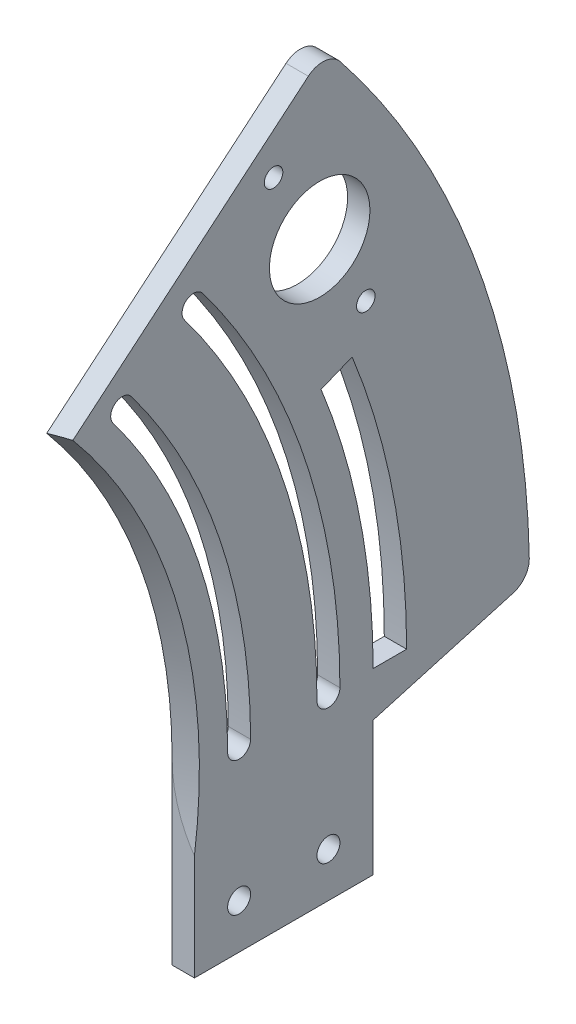
SolidWorks part; units mm, degrees
material "ABS"
ref_plane "Front Plane" through (0, 0, 0) normal (0, 0, 1) x (1, 0, 0)
ref_plane "Top Plane" through (0, 0, 0) normal (0, 1, 0) x (1, 0, 0)
ref_plane "Right Plane" through (0, 0, 0) normal (1, 0, 0) x (0, 0, -1)
sketch "Sketch1" plane through (0, 0, 0) normal (1, 0, 0) x (0, 0, -1)
  line L0 (-1000, 0) -> (49000, 0) construction
  line L1 (0, 0) -> (116.7452, 97.9608) construction
  line L2 (0, 0) -> (59.8729, -43.5002) construction
  line L3 (152.4, 0) -> (152.4, -50.8)
  line L5 (152.4, -50.8) -> (203.2, -50.8)
  line L6 (203.2, -50.8) -> (203.2, 0)
  line L7 (155.6602, 130.6144) -> (189.7109, 159.1864)
  line L8 (-23.5062, -9.499) -> (46248.5759, 18689.3257) construction
  line L9 (188.3985, 76.133) -> (229.6107, 92.7871)
  line L10 (0, 0) -> (188.0059, 113.3006) construction
  line L11 (186.339, 99.7277) -> (-5908.5361, -49527.4069) construction
  line L12 (188.0059, 113.3006) -> (49815.1406, -5981.5745) construction
  line L13 (0, 0) -> (190.9455, 69.4985) construction
  line L16 (116.7452, 97.9608) -> (155.6602, 130.6144)
  line L17 (190.9455, 69.4985) -> (202.8796, 73.8421) construction
  line L20 (190.9455, 69.4985) -> (196.9126, 71.6703) construction
  line L21 (188.0059, 113.3006) -> (-25619.9772, 42937.9197) construction
  arc A0 (152.4, 0) -> (116.7452, 97.9608) centre (0, 0) ccw
  arc A2 (189.7109, 159.1864) -> (229.6107, 92.7871) centre (0, 0) cw
  circle A3 centre (188.0059, 113.3006) radius 14.2875
  circle A4 centre (188.0059, 113.3006) radius 25.4 construction
  circle A12 centre (174.8954, 135.0555) radius 2.6289
  arc A13 (190.9455, 69.4985) -> (203.2, 0) centre (0, 0) cw
  arc A14 (190.9455, 69.4985) -> (188.3985, 76.133) centre (0, 0) ccw
  circle A15 centre (201.1164, 91.5456) radius 2.6289
  point P9 (183.2534, 74.6033)
  dimension "D1" = 304.8
  dimension "D11" = 28.575
  dimension "D12" = 50.8
  dimension "D14" = 50.8
  dimension "D15" = 9.525
  dimension "D7" = 5.2578
  dimension "D8" = 5.2578
  dimension "D2" = 40
  dimension "D3" = 36
  dimension "D4" = 50.8
  dimension "D5" = 50.8
  dimension "D6" = 44.45
  dimension "D9" = 219.5068
  dimension "D10" = 8.925
  dimension "D13" = 90
  dimension "D16" = 20
  dimension "D17" = 12.7
extrude "Boss-Extrude1" add sketch "Sketch1" along normal blind 6.35
sketch "Sketch2" plane through (6.35, 0, 0) normal (1, 0, 0) x (0, 0, -1)
  line L0 (-1000, 0) -> (49000, 0) construction
  line L1 (0, 0) -> (218.1696, 164.4026) construction
  arc A1 (152.4, 0) -> (116.7452, 97.9608) centre (0, 0) ccw construction
  arc A2 (134.4614, 101.3239) -> (129.2481, 97.3954) centre (131.8547, 99.3597) ccw
  arc A3 (129.2481, 97.3954) -> (161.8361, 0) centre (0, 0) cw
  arc A4 (134.4614, 101.3239) -> (168.3639, 0) centre (0, 0) cw
  arc A5 (161.8361, 0) -> (168.3639, 0) centre (165.1, 0) ccw
  arc A6 (154.7467, 116.61) -> (149.5334, 112.6815) centre (152.1401, 114.6458) ccw
  arc A7 (149.5334, 112.6815) -> (187.2361, 0) centre (0, 0) cw
  arc A8 (154.7467, 116.61) -> (193.7639, 0) centre (0, 0) cw
  arc A9 (152.1401, 114.6458) -> (190.5, 0) centre (0, 0) cw construction
  arc A10 (187.2361, 0) -> (193.7639, 0) centre (190.5, 0) ccw
  point P9 (131.8547, 99.3597)
  point P14 (152.1401, 114.6458)
  point P19 (165.1, 0)
  dimension "D3" = 6.5278
  dimension "D5" = 6.5278
  dimension "D1" = 37
  dimension "D2" = 165.1
  dimension "D4" = 25.4
extrude "Cut-Extrude4" cut sketch "Sketch2" against normal blind 6.35
sketch "Sketch3" plane through (6.35, 0, 0) normal (1, 0, 0) x (0, 0, -1)
  line L0 (165.1, -38.1) -> (190.5, -38.1) construction
  line L1 (152.4, -50.8) -> (165.1, -50.8) construction
  line L2 (152.4, -50.8) -> (152.4, -38.1) construction
  line L3 (152.4, -38.1) -> (165.1, -38.1) construction
  line L4 (165.1, -50.8) -> (165.1, -38.1) construction
  circle A0 centre (165.1, -38.1) radius 3.2639
  circle A1 centre (190.5, -38.1) radius 3.2639
  dimension "D3" = 6.5278
  dimension "D5" = 6.5278
  dimension "D1" = 12.7
  dimension "D2" = 12.7
  dimension "D4" = 25.4
extrude "Cut-Extrude5" cut sketch "Sketch3" against normal blind 6.35
fillet "Fillet1" radius 6.35 1 edges at (3.175, 159.1864, -189.7109)
sketch "Sketch4" plane through (0, 0, 0) normal (0, 1, 0) x (1, 0, 0)
  line L0 (0, 0) -> (0, 152.4) construction
  line L1 (0, 0) -> (28.575, 0) construction
  line L2 (28.575, 0) -> (28.575, 38.1) construction
  line L3 (-89.2427, 38.1) -> (146.3927, 38.1)
  line L4 (-1000, 0) -> (49000, 0) construction
  arc A0 (146.3927, 38.1) -> (-89.2427, 38.1) centre (28.575, 38.1) ccw
  dimension "D1" = 152.4
  dimension "D2" = 28.575
  dimension "D3" = 38.1
revolve "Cut-Revolve1" cut sketch "Sketch4" angle 360 about L4
sketch "Sketch5" plane through (0, 0, 0) normal (-1, 0, 0) x (0, 0, 1)
  line L0 (-188.3985, 76.133) -> (-229.6107, 92.7871) construction
  line L1 (-197.2297, 79.7017) -> (-229.6107, 92.7871)
  line L2 (-247.65, 0) -> (-212.725, 0) construction
  line L3 (-212.725, 0) -> (-203.2, 0)
  line L4 (-247.65, 0) -> (-203.2, -12.7)
  line L5 (-203.2, -50.8) -> (-203.2, 0) construction
  line L6 (-203.2, -12.7) -> (-203.2, 0)
  arc A0 (-212.725, 0) -> (-197.2297, 79.7017) centre (0, 0) cw
  arc A1 (-188.3985, 76.133) -> (-203.2, 0) centre (0, 0) ccw construction
  arc A2 (-229.6107, 92.7871) -> (-247.65, 0) centre (0, 0) ccw
  dimension "D1" = 9.525
  dimension "D2" = 34.925
  dimension "D3" = 12.7
extrude "Boss-Extrude2" add sketch "Sketch5" against normal blind 6.35
fillet "Fillet3" radius 6.35 1 edges at (3.175, 0, -247.65)
